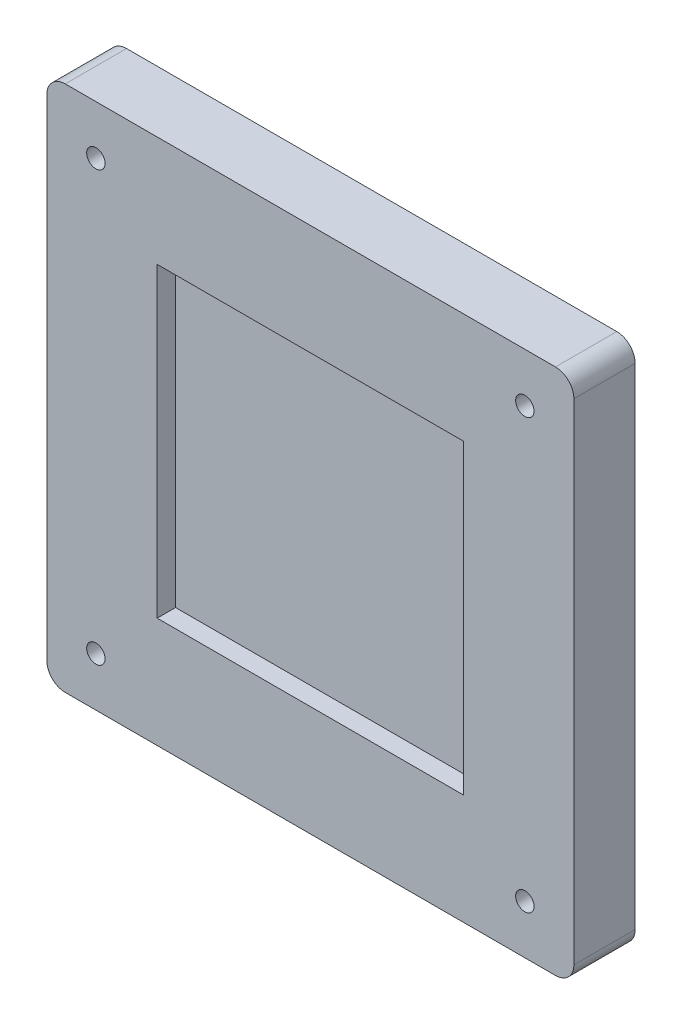
SolidWorks part; units mm, degrees
ref_plane "前视基准面" through (0, 0, 0) normal (0, 0, 1) x (1, 0, 0)
ref_plane "上视基准面" through (0, 0, 0) normal (0, 1, 0) x (1, 0, 0)
ref_plane "右视基准面" through (0, 0, 0) normal (1, 0, 0) x (0, 0, -1)
sketch "草图1" plane through (0, 0, 0) normal (0, 0, 1) x (1, 0, 0)
  line L0 (-40, -43) -> (40, -43)
  line L1 (43, -40) -> (43, 40)
  line L2 (40, 43) -> (-40, 43)
  line L3 (-43, 40) -> (-43, -40)
  arc A0 (-43, -40) -> (-40, -43) centre (-40, -40) ccw
  arc A1 (40, -43) -> (43, -40) centre (40, -40) ccw
  arc A2 (43, 40) -> (40, 43) centre (40, 40) ccw
  arc A3 (-40, 43) -> (-43, 40) centre (-40, 40) ccw
extrude "凸台-拉伸1" add sketch "草图1" along normal blind 10
ref_plane "基准面1" through (0, 0, 10) normal (0, 0, 1) x (1, 0, 0)
sketch "草图2" plane through (0, 0, 10) normal (0, 0, 1) x (1, 0, 0)
  line L0 (-25, -25) -> (25, -25)
  line L1 (25, -25) -> (25, 25)
  line L2 (25, 25) -> (-25, 25)
  line L3 (-25, 25) -> (-25, -25)
extrude "切除-拉伸1" cut sketch "草图2" against normal blind 3
sketch "草图3" plane through (0, 0, 10) normal (0, 0, 1) x (1, 0, 0)
  circle A0 centre (-35, -35) radius 1.5
  circle A1 centre (-35, 35) radius 1.5
  circle A2 centre (35, -35) radius 1.5
  circle A3 centre (35, 35) radius 1.5
extrude "切除-拉伸2" cut sketch "草图3" against normal mid plane 174
